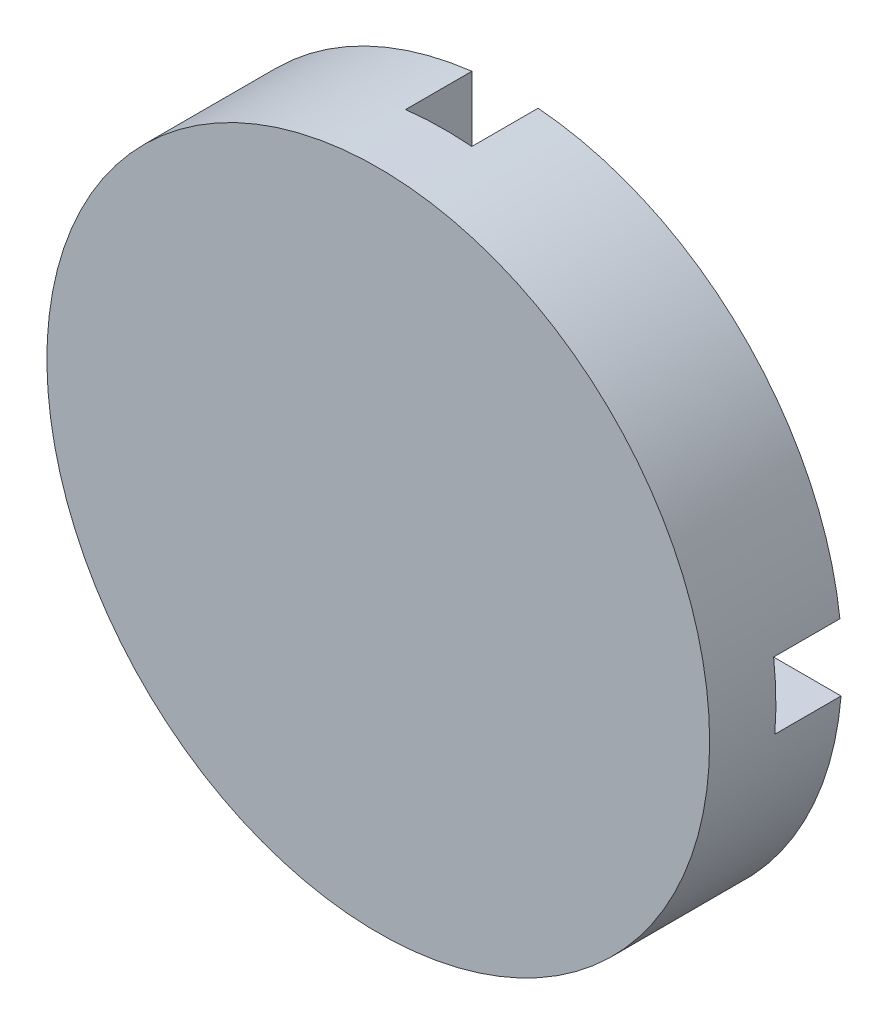
SolidWorks part; units mm, degrees
ref_plane "Front Plane" through (0, 0, 0) normal (0, 0, 1) x (1, 0, 0)
ref_plane "Top Plane" through (0, 0, 0) normal (0, 1, 0) x (1, 0, 0)
ref_plane "Right Plane" through (0, 0, 0) normal (1, 0, 0) x (0, 0, -1)
sketch "Sketch2" plane through (0, 0, 0) normal (0, 0, 1) x (1, 0, 0)
  line L2 (4.1204, 49.8299) -> (4.1204, 5.8794)
  line L3 (-5.8796, 49.6531) -> (-5.8796, 5.8794)
  line L4 (-49.6531, 5.8794) -> (-5.8796, 5.8794)
  line L5 (-49.8299, -4.1206) -> (-5.8796, -4.1206)
  line L6 (-5.8796, -4.1206) -> (-5.8796, -49.6531)
  line L7 (4.1204, -4.1206) -> (4.1204, -49.8299)
  line L8 (4.1204, 5.8794) -> (49.6531, 5.8794)
  line L9 (4.1204, -4.1206) -> (49.8299, -4.1206)
  arc A0 (-5.8796, 49.6531) -> (-49.6531, 5.8794) centre (0, 0) ccw
  arc A1 (-49.8299, -4.1206) -> (-5.8796, -49.6531) centre (0, 0) ccw
  arc A2 (4.1204, -49.8299) -> (49.8299, -4.1206) centre (0, 0) ccw
  arc A3 (49.6531, 5.8794) -> (4.1204, 49.8299) centre (0, 0) ccw
  point P6 (0, 0)
  point P9 (0, 0)
  point P10 (0, 0)
  point P13 (4.1204, 0)
  point P16 (-4.0966, 0)
  point P19 (0, 5.8794)
  point P22 (0, -5.7378)
extrude "Boss-Extrude1" add sketch "Sketch2" along normal blind 10
sketch "Sketch3" plane through (0, 0, 10) normal (0, 0, 1) x (1, 0, 0)
  circle A0 centre (0, 0) radius 50
extrude "Boss-Extrude2" add sketch "Sketch3" along normal blind 10
